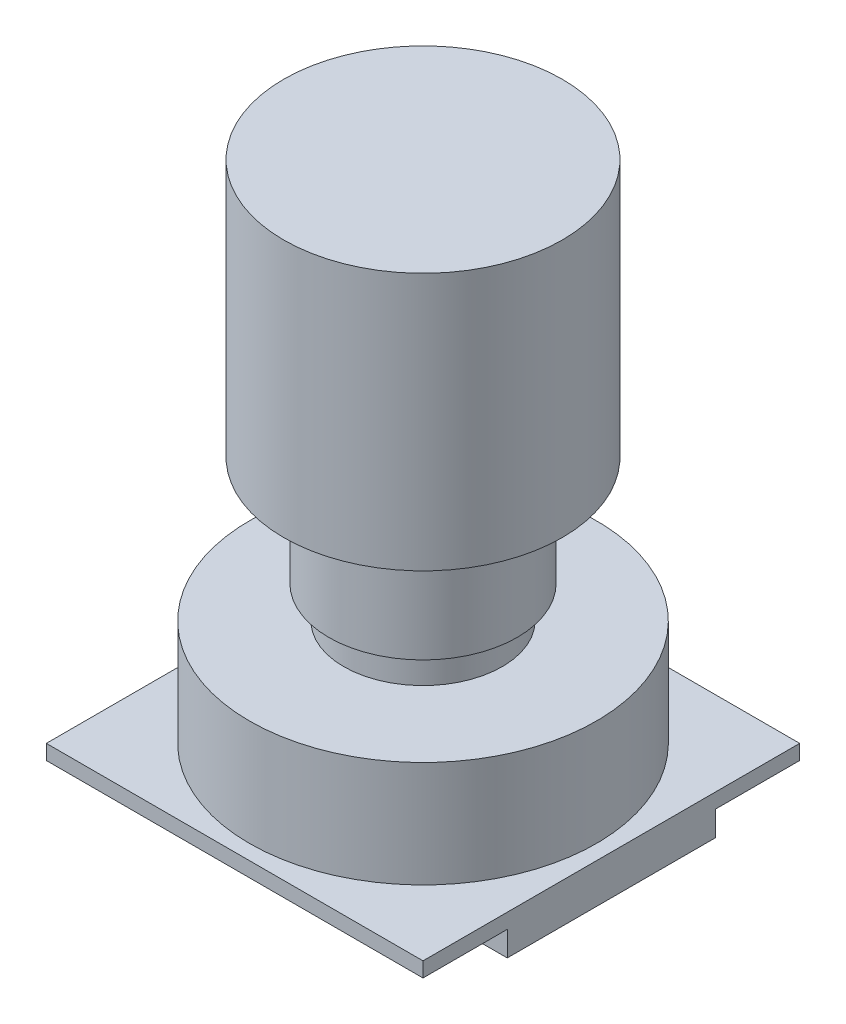
SolidWorks part; units mm, degrees
ref_plane "Front Plane" through (0, 0, 0) normal (0, 0, 1) x (1, 0, 0)
ref_plane "Top Plane" through (0, 0, 0) normal (0, 1, 0) x (1, 0, 0)
ref_plane "Right Plane" through (0, 0, 0) normal (1, 0, 0) x (0, 0, -1)
sketch "Sketch1" plane through (0, 0, 0) normal (0, 1, 0) x (1, 0, 0)
  line L1 (-19, -19) -> (19, -19)
  line L2 (-19, -19) -> (-19, 19)
  line L3 (-19, 19) -> (19, 19)
  line L4 (19, -19) -> (19, 19)
  line L5 (-19, -19) -> (19, 19) construction
  line L6 (-19, 19) -> (19, -19) construction
  point P0 (0, 0)
  dimension "D1" = 38
extrude "Boss-Extrude1" add sketch "Sketch1" along normal blind 1.5
sketch "Sketch2" plane through (0, 1.5, 0) normal (0, 1, 0) x (1, 0, 0)
  circle A0 centre (0, 0) radius 17.5
  dimension "D1" = 35
extrude "Boss-Extrude2" add sketch "Sketch2" along normal blind 10.7
sketch "Sketch3" plane through (0, 12.2, 0) normal (0, 1, 0) x (1, 0, 0)
  circle A0 centre (0, 0) radius 8
  dimension "D1" = 16
extrude "Boss-Extrude3" add sketch "Sketch3" along normal blind 3.3
sketch "Sketch4" plane through (0, 15.5, 0) normal (0, 1, 0) x (1, 0, 0)
  circle A0 centre (0, 0) radius 9.5
  dimension "D1" = 19
extrude "Boss-Extrude4" add sketch "Sketch4" along normal blind 11
sketch "Sketch5" plane through (0, 26.5, 0) normal (0, 1, 0) x (1, 0, 0)
  circle A0 centre (0, 0) radius 14.05
  dimension "D1" = 28.1
extrude "Boss-Extrude5" add sketch "Sketch5" along normal blind 26
sketch "Sketch7" plane through (0, 0, 0) normal (0, -1, 0) x (1, 0, 0)
  line L0 (19, 19) -> (19, -19) construction
  line L1 (19, -10.5) -> (13, -10.5)
  line L2 (19, -10.5) -> (19, 10.5)
  line L3 (19, 10.5) -> (13, 10.5)
  line L4 (13, -10.5) -> (13, 10.5)
  line L5 (19, -19) -> (-19, -19) construction
  line L6 (-19, 19) -> (19, 19) construction
  dimension "D1" = 8.5
  dimension "D2" = 8.5
  dimension "D3" = 6
extrude "Boss-Extrude6" add sketch "Sketch7" along normal blind 2.5
equation "\"D1@Boss-Extrude2\"=12.2-1.5"
equation "\"D1@Boss-Extrude6\"=4-1.5"
